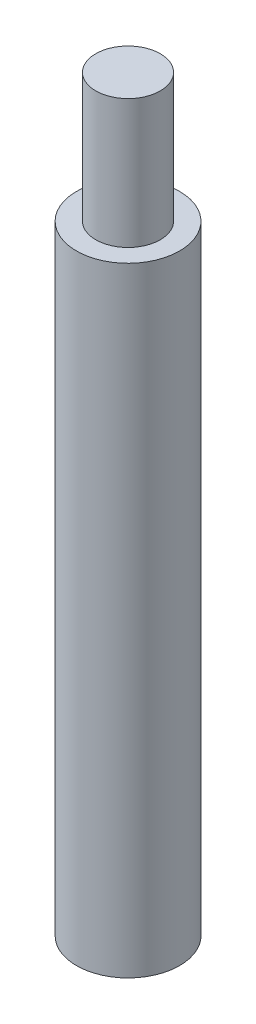
SolidWorks part; units mm, degrees
ref_plane "Alzado" through (0, 0, 0) normal (0, 0, 1) x (1, 0, 0)
ref_plane "Planta" through (0, 0, 0) normal (0, 1, 0) x (1, 0, 0)
ref_plane "Vista lateral" through (0, 0, 0) normal (1, 0, 0) x (0, 0, -1)
sketch "Croquis1" plane through (0, 0, 0) normal (0, 0, 1) x (1, 0, 0)
  line L0 (0, 0) -> (0, 116)
  line L1 (0, 116) -> (-5, 116)
  line L2 (-5, 116) -> (-5, 96)
  line L3 (-5, 96) -> (-8, 96)
  line L4 (-8, 96) -> (-8, 0)
  line L5 (-8, 0) -> (0, 0)
  dimension "D1" = 96
  dimension "D2" = 8
  dimension "D3" = 5
  dimension "D4" = 20
revolve "Revolución1" add sketch "Croquis1" angle 360 about L0
